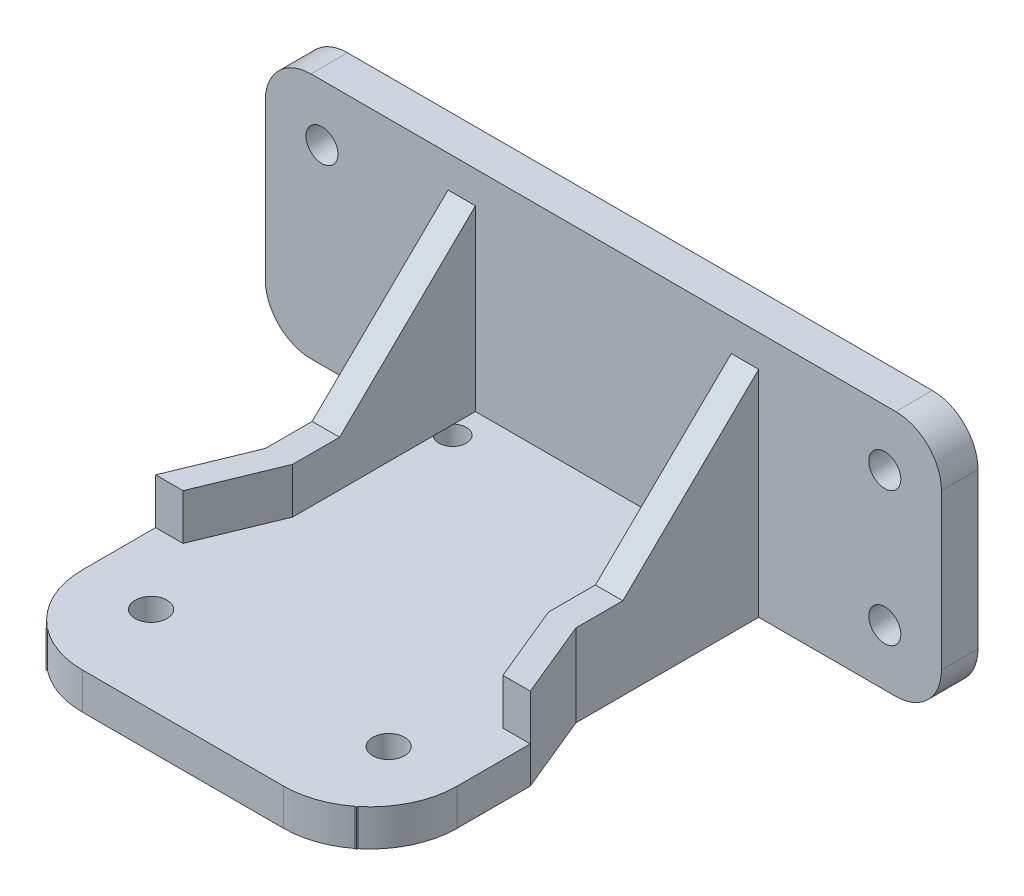
SolidWorks part; units mm, degrees
ref_plane "前视基准面" through (0, 0, 0) normal (0, 0, 1) x (1, 0, 0)
ref_plane "上视基准面" through (0, 0, 0) normal (0, 1, 0) x (1, 0, 0)
ref_plane "右视基准面" through (0, 0, 0) normal (1, 0, 0) x (0, 0, -1)
sketch "草图1" plane through (0, 0, 0) normal (0, 0, 1) x (1, 0, 0)
  line L1 (-17, -25.5) -> (17, -25.5)
  line L2 (-17, -25.5) -> (-17, 25.5)
  line L3 (-17, 25.5) -> (17, 25.5)
  line L4 (17, -25.5) -> (17, 25.5)
  line L5 (-17, -25.5) -> (17, 25.5) construction
  line L6 (-17, 25.5) -> (17, -25.5) construction
  point P0 (0, 0)
  dimension "D1" = 34
  dimension "D2" = 51
extrude "凸台-拉伸1" add sketch "草图1" along normal blind 4
sketch "草图5" plane through (0, -25.5, 0) normal (0, -1, 0) x (1, 0, 0)
  line L0 (0, 4) -> (0, 0) construction
  line L1 (-17, 4) -> (17, 4) construction
  line L7 (17, 0) -> (-17, 0)
  line L8 (17, 0) -> (17, 15)
  line L9 (17, 15) -> (-17, 15)
  line L10 (-17, 0) -> (-17, 15)
  point P5 (0, 2)
  dimension "D1" = 15
  dimension "D2" = 34
extrude "凸台-拉伸2" add sketch "草图5" along normal blind 4
sketch "草图6" plane through (0, -29.5, 0) normal (0, -1, 0) x (1, 0, 0)
  line L0 (0, 0) -> (0, 7.5) construction
  line L3 (0, 7.5) -> (13, 7.5) construction
  circle A4 centre (13, 7.5) radius 1.5
  circle A5 centre (-13, 7.5) radius 1.5
  point P6 (0, 2)
  dimension "D3" = 3
  dimension "D1" = 7.5
  dimension "D2" = 13
extrude "切除-拉伸3" cut sketch "草图6" against normal blind 4
sketch "草图9" plane through (0, -25.5, 0) normal (0, 1, 0) x (1, 0, 0)
  line L0 (0, -15) -> (0, -4) construction
  line L1 (17, -15) -> (-17, -15) construction
  line L2 (17, -4) -> (-17, -4) construction
  line L3 (0, -15) -> (10, -15) construction
  line L4 (0, -15) -> (-10, -15) construction
  line L6 (-10, -15) -> (-7, -15)
  line L7 (-10, -15) -> (-10, -4)
  line L8 (-10, -4) -> (-7, -4)
  line L9 (-7, -15) -> (-7, -4)
  line L10 (10, -15) -> (7, -15)
  line L11 (10, -15) -> (10, -4)
  line L12 (10, -4) -> (7, -4)
  line L13 (7, -15) -> (7, -4)
  line L14 (-17, -4) -> (17, -4) construction
  dimension "D1" = 10
  dimension "D2" = 10
  dimension "D3" = 11
  dimension "D4" = 3
  dimension "D5" = 11
  dimension "D6" = 3
sketch "草图12" plane through (0, 25.5, 0) normal (0, 1, 0) x (1, 0, 0)
  line L4 (17, 0) -> (-17, 0)
  line L5 (-17, 0) -> (-17, -4)
  line L6 (-17, -4) -> (17, -4)
  line L7 (17, -4) -> (17, 0)
  line L8 (17, 0) -> (-17, 0)
  line L9 (-17, 0) -> (-17, -4)
  line L10 (-17, -4) -> (17, -4)
  line L11 (17, -4) -> (17, 0)
  dimension "D1" = 0
extrude "切除-拉伸5" cut sketch "草图12" against normal blind 5
sketch "草图13" plane through (0, 20.5, 0) normal (0, 1, 0) x (1, 0, 0)
  line L4 (17, -4) -> (17, 0)
  line L5 (17, 0) -> (-17, 0)
  line L6 (-17, 0) -> (-17, -4)
  line L7 (-17, -4) -> (17, -4)
  line L8 (17, -4) -> (17, 0)
  line L9 (17, 0) -> (-17, 0)
  line L10 (-17, 0) -> (-17, -4)
  line L11 (-17, -4) -> (17, -4)
  dimension "D1" = 0
extrude "切除-拉伸6" cut sketch "草图13" against normal blind 7
sketch "草图14" plane through (0, 0, 15) normal (0, 0, 1) x (1, 0, 0)
  line L4 (17, -25.5) -> (-17, -25.5)
  line L5 (-17, -25.5) -> (-17, -29.5)
  line L6 (-17, -29.5) -> (17, -29.5)
  line L7 (17, -29.5) -> (17, -25.5)
  line L8 (17, -25.5) -> (-17, -25.5)
  line L9 (-17, -25.5) -> (-17, -29.5)
  line L10 (-17, -29.5) -> (17, -29.5)
  line L11 (17, -29.5) -> (17, -25.5)
  dimension "D1" = 0
extrude "凸台-拉伸3" add sketch "草图14" along normal blind 33
sketch "草图15" plane through (0, -25.5, 0) normal (0, 1, 0) x (1, 0, 0)
  line L0 (-13, -7.5) -> (-13, -40.5) construction
  line L1 (-13, -7.5) -> (13, -7.5) construction
  line L2 (13, -7.5) -> (13, -40.5) construction
  circle A0 centre (13, -40.5) radius 1.75
  circle A1 centre (-13, -40.5) radius 1.75
  dimension "D2" = 3.5
  dimension "D3" = 3.5
  dimension "D1" = 33
extrude "切除-拉伸7" cut sketch "草图15" against normal blind 44
sketch "草图16" plane through (-17, 0, 0) normal (-1, 0, 0) x (0, 0, 1)
  line L0 (4, -25.5) -> (4, -6)
  line L2 (4, 13.5) -> (4, -25.5) construction
  line L3 (4, -25.5) -> (24, -25.5) construction
  line L4 (48, -25.5) -> (4, -25.5) construction
  line L5 (4, -6) -> (24, -25.5)
  line L6 (24, -25.5) -> (4, -25.5)
  dimension "D1" = 19.5
  dimension "D2" = 20
extrude "凸台-拉伸4" add sketch "草图16" against normal blind 3
sketch "草图17" plane through (17, 0, 0) normal (1, 0, 0) x (0, 0, -1)
  line L0 (-24, -25.5) -> (-4, -6) construction
  line L1 (-24, -25.5) -> (-4, -6)
  line L2 (-24, -25.5) -> (-4, -25.5)
  line L3 (-4, -25.5) -> (-4, -6)
extrude "凸台-拉伸5" add sketch "草图17" against normal blind 3
sketch "草图18" plane through (0, -25.5, 0) normal (0, 1, 0) x (1, 0, 0)
  line L3 (20.499, -32.5) -> (17, -24)
  line L4 (-20.501, -32.5) -> (-17, -24)
  line L5 (-17, -24) -> (17, -24)
  line L6 (20.499, -32.5) -> (20.499, -40.5)
  line L7 (10.999, -50) -> (-11.001, -50)
  line L8 (-20.501, -40.5) -> (-20.501, -32.5)
  circle A2 centre (-13, -40.5) radius 1.75
  circle A3 centre (13, -40.5) radius 1.75
  arc A4 (10.999, -50) -> (20.499, -40.5) centre (10.999, -40.5) ccw
  arc A5 (-20.501, -40.5) -> (-11.001, -50) centre (-11.001, -40.5) ccw
extrude "凸台-拉伸6" add sketch "草图18" against normal blind 4
sketch "草图19" plane through (0, -25.5, 0) normal (0, 1, 0) x (1, 0, 0)
  line L0 (-20.501, -32.5) -> (-17.501, -32.5)
  line L1 (-17.501, -32.5) -> (-14, -24)
  line L3 (-17, -24) -> (-20.501, -32.5)
  line L5 (17, -24) -> (20.499, -32.5)
  line L6 (20.499, -32.5) -> (17.499, -32.5)
  line L7 (17.499, -32.5) -> (14, -24)
  line L8 (-17, -24) -> (-17, -16)
  line L9 (-17, -24) -> (-17, -4) construction
  line L10 (-17, -16) -> (-14, -16)
  line L11 (-14, -8.618) -> (-14, -24) construction
  line L12 (-14, -16) -> (-14, -24)
  line L13 (14, -24) -> (14, -16)
  line L14 (14, -16) -> (17, -16)
  line L15 (17, -4) -> (17, -24) construction
  line L16 (17, -16) -> (17, -24)
  dimension "D1" = 3
  dimension "D2" = 3
  dimension "D3" = 8
extrude "凸台-拉伸7" add sketch "草图19" along normal blind 5
sketch "草图20" plane through (17, 0, 0) normal (1, 0, 0) x (0, 0, -1)
  line L1 (0, 13.5) -> (-4, 13.5)
  line L2 (0, 13.5) -> (0, -29.5)
  line L3 (0, -29.5) -> (-4, -29.5)
  line L4 (-4, 13.5) -> (-4, -29.5)
  line L5 (0, -29.5) -> (-24, -29.5) construction
  dimension "D1" = 43
  dimension "D2" = 4
extrude "凸台-拉伸8" add sketch "草图20" along normal blind 20
sketch "草图21" plane through (-17, 0, 0) normal (-1, 0, 0) x (0, 0, 1)
  line L1 (0, 13.5) -> (4, 13.5)
  line L2 (0, 13.5) -> (0, -29.5)
  line L3 (0, -29.5) -> (4, -29.5)
  line L4 (4, 13.5) -> (4, -29.5)
extrude "凸台-拉伸9" add sketch "草图21" along normal blind 20
sketch "草图22" plane through (0, 13.5, 0) normal (0, 1, 0) x (1, 0, 0)
  line L4 (-37, -4) -> (37, -4)
  line L5 (37, -4) -> (37, 0)
  line L6 (37, 0) -> (-37, 0)
  line L7 (-37, 0) -> (-37, -4)
  line L8 (-37, -4) -> (37, -4)
  line L9 (37, -4) -> (37, 0)
  line L10 (37, 0) -> (-37, 0)
  line L11 (-37, 0) -> (-37, -4)
  dimension "D1" = 0
extrude "切除-拉伸8" cut sketch "草图22" against normal blind 16
sketch "草图23" plane through (0, 0, 0) normal (0, 0, -1) x (-1, 0, 0)
  line L0 (-37, -16) -> (37, -16) construction
  line L1 (-37, -29.5) -> (-37, -2.5) construction
  line L2 (37, -2.5) -> (37, -29.5) construction
  line L3 (0, -16) -> (30.8, -16) construction
  line L4 (30.8, -16) -> (30.8, -8.65) construction
  line L5 (0, -2.5) -> (0, -29.5) construction
  line L6 (-37, -2.5) -> (37, -2.5) construction
  line L7 (37, -29.5) -> (-37, -29.5) construction
  line L8 (-30.8, -23.35) -> (20.15, -23.35) construction
  circle A0 centre (30.8, -8.65) radius 1.75
  circle A1 centre (-30.8, -8.65) radius 1.75
  circle A3 centre (-30.8, -23.35) radius 1.75
  circle A4 centre (20.15, -23.35) radius 1.75
  dimension "D3" = 3.5
  dimension "D5" = 3.5
  dimension "D1" = 30.8
  dimension "D2" = 7.35
  dimension "D4" = 50.95
extrude "切除-拉伸9" cut sketch "草图23" against normal blind 16
fillet "圆角1" radius 5 4 edges at (37, -29.5, 2) (37, -2.5, 2) (-37, -2.5, 2) (-37, -29.5, 2)
